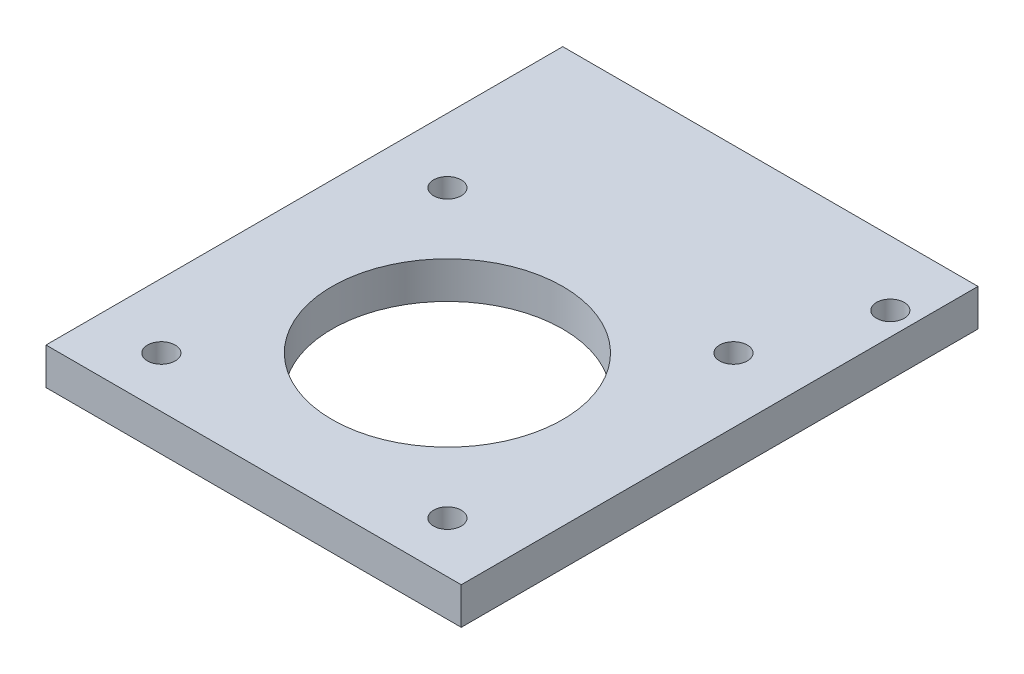
SolidWorks part; units mm, degrees
ref_plane "Plano frontal" through (0, 0, 0) normal (0, 0, 1) x (1, 0, 0)
ref_plane "Plano superior" through (0, 0, 0) normal (0, 1, 0) x (1, 0, 0)
ref_plane "Plano direito" through (0, 0, 0) normal (1, 0, 0) x (0, 0, -1)
sketch "Esboço1" plane through (0, 0, 0) normal (0, 1, 0) x (1, 0, 0)
  line L1 (-22.5, 28) -> (22.5, 28)
  line L2 (-22.5, 28) -> (-22.5, -28)
  line L3 (-22.5, -28) -> (22.5, -28)
  line L4 (22.5, 28) -> (22.5, -28)
  line L5 (-22.5, 28) -> (22.5, -28) construction
  line L6 (-22.5, -28) -> (22.5, 28) construction
  point P0 (0, 0)
  dimension "D1" = 45
  dimension "D2" = 56
extrude "Ressalto-extrusão1" add sketch "Esboço1" along normal blind 4
sketch "Esboço4" plane through (0, 4, 0) normal (0, 1, 0) x (1, 0, 0)
  line L0 (0, 28) -> (0, -7) construction
  line L1 (22.5, 28) -> (-22.5, 28) construction
  line L2 (0, -7) -> (15.5, -7) construction
  line L3 (15.5, -7) -> (15.5, 8.5) construction
  line L4 (15.5, 8.5) -> (-15.5, 8.5) construction
  line L5 (-15.5, 8.5) -> (-15.5, -22.5) construction
  line L6 (-15.5, -22.5) -> (15.5, -22.5) construction
  line L7 (0, -7) -> (0, 21) construction
  line L8 (0, 21) -> (20, 21) construction
  circle A0 centre (-15.5, 8.5) radius 1.5
  circle A1 centre (-15.5, -22.5) radius 1.5
  circle A2 centre (15.5, -22.5) radius 1.5
  circle A3 centre (15.5, 8.5) radius 1.5
  circle A4 centre (20, 21) radius 1.5
  circle A5 centre (0, -7) radius 12.5
  dimension "D7" = 20
  dimension "D8" = 25
  dimension "D1" = 35
  dimension "D2" = 15.5
  dimension "D3" = 15.5
  dimension "D4" = 31
  dimension "D5" = 31
  dimension "D6" = 31
extrude "Corte-extrusão1" cut sketch "Esboço4" against normal through all
